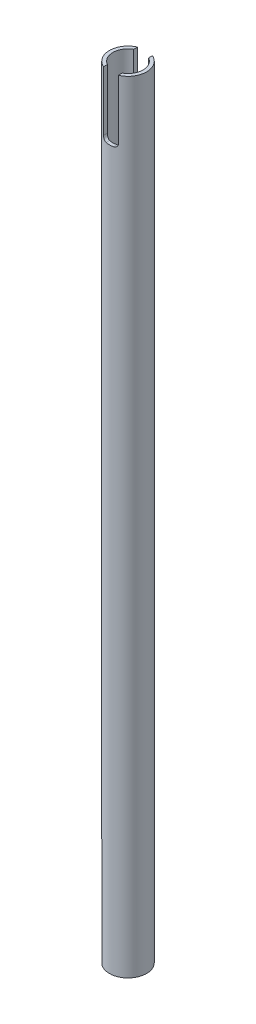
SolidWorks part; units mm, degrees
material "AISI 4130 Steel, normalized at 870C"
ref_plane "X-Y Datum" through (0, 0, 0) normal (0, 0, 1) x (1, 0, 0)
ref_plane "X-Z Datum" through (0, 0, 0) normal (0, 1, 0) x (1, 0, 0)
ref_plane "Y-Z Datum" through (0, 0, 0) normal (1, 0, 0) x (0, 0, -1)
sketch "Sketch1" plane through (0, 0, 0) normal (0, 1, 0) x (1, 0, 0)
  circle A0 centre (0, 0) radius 7.9375
  circle A1 centre (0, 0) radius 6.4643
  dimension "D1" = 1.4732
  dimension "D2" = 15.875
extrude "Boss-Extrude1" add sketch "Sketch1" along normal offset from surface (333.5622 mm away) 25.4 from surface at -163.4167
sketch "Sketch2" plane through (0, 0, 0) normal (0, 0, 1) x (1, 0, 0)
  line L0 (0, 170.1455) -> (0, 143.158) construction
  line L1 (-3.175, 170.1455) -> (3.175, 170.1455)
  line L3 (-1.5875, 143.158) -> (1.5875, 143.158)
  line L4 (3.175, 170.1455) -> (3.175, 144.7455)
  line L6 (-3.175, 170.1455) -> (-3.175, 144.7455)
  line L7 (6.4643, 170.1455) -> (-6.4643, 170.1455) construction
  arc A0 (-3.175, 144.7455) -> (-1.5875, 143.158) centre (-1.5875, 144.7455) ccw
  arc A1 (1.5875, 143.158) -> (3.175, 144.7455) centre (1.5875, 144.7455) ccw
  dimension "D2" = 1.5875
extrude "Cut-Extrude1" cut sketch "Sketch2" against normal through all both and the other way through all
